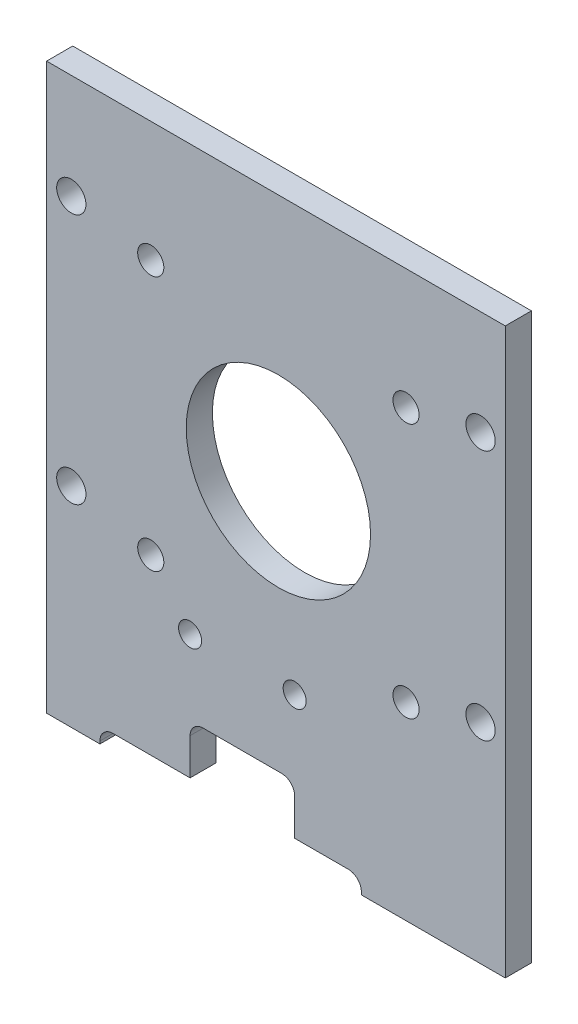
SolidWorks part; units mm, degrees
ref_plane "Front Plane" through (0, 0, 0) normal (0, 0, 1) x (1, 0, 0)
ref_plane "Top Plane" through (0, 0, 0) normal (0, 1, 0) x (1, 0, 0)
ref_plane "Right Plane" through (0, 0, 0) normal (1, 0, 0) x (0, 0, -1)
sketch "Sketch1" plane through (0, 0, 0) normal (0, 0, 1) x (1, 0, 0)
  line L1 (0, 0) -> (55.7007, 0)
  line L2 (0, 0) -> (0, 68.58)
  line L3 (0, 68.58) -> (55.7007, 68.58)
  line L4 (55.7007, 0) -> (55.7007, 68.58)
  dimension "D1" = 55.7007
  dimension "D2" = 68.58
extrude "Boss-Extrude1" add sketch "Sketch1" along normal blind 3.175
sketch "Sketch2" plane through (0, 0, 3.175) normal (0, 0, 1) x (1, 0, 0)
  line L0 (22.8992, 38.475) -> (24.6492, 38.475) construction
  line L1 (12.6492, 22.975) -> (43.6492, 22.975) construction
  line L2 (12.6492, 22.975) -> (12.6492, 53.975) construction
  line L3 (12.6492, 53.975) -> (43.6492, 53.975) construction
  line L4 (43.6492, 22.975) -> (43.6492, 53.975) construction
  line L5 (12.6492, 22.975) -> (43.6492, 53.975) construction
  line L6 (12.6492, 53.975) -> (43.6492, 22.975) construction
  line L7 (55.7007, 68.58) -> (0, 68.58) construction
  line L8 (0, 68.58) -> (0, 0) construction
  line L9 (23.7742, 38.475) -> (23.7742, 17.0053) construction
  line L10 (23.7742, 17.0053) -> (30.1242, 17.0053) construction
  line L11 (23.7742, 17.0053) -> (17.4242, 17.0053) construction
  line L13 (7.1492, 17.475) -> (49.1492, 17.475) construction
  line L14 (7.1492, 17.475) -> (7.1492, 59.475) construction
  line L15 (7.1492, 59.475) -> (49.1492, 59.475) construction
  line L16 (49.1492, 17.475) -> (49.1492, 59.475) construction
  line L17 (7.1492, 17.475) -> (49.1492, 59.475) construction
  line L18 (7.1492, 59.475) -> (49.1492, 17.475) construction
  line L20 (0, 0) -> (55.7007, 0) construction
  line L21 (17.4242, 0) -> (30.1242, 0)
  line L22 (17.4242, 0) -> (17.4242, 7.9375)
  line L23 (17.4242, 7.9375) -> (30.1242, 7.9375)
  line L24 (30.1242, 0) -> (30.1242, 7.9375)
  line L25 (23.7742, 17.0053) -> (23.7742, 7.9375) construction
  circle A0 centre (28.1492, 38.475) radius 11.1905
  circle A1 centre (12.6492, 53.975) radius 1.5875
  circle A2 centre (43.6492, 53.975) radius 1.5875
  circle A3 centre (43.6492, 22.975) radius 1.5875
  circle A4 centre (12.6492, 22.975) radius 1.5875
  circle A5 centre (11.8992, 38.475) radius 11 construction
  circle A6 centre (28.1492, 38.475) radius 3.5 construction
  circle A7 centre (17.4242, 17.0053) radius 1.397
  circle A8 centre (30.1242, 17.0053) radius 1.397
  dimension "D1" = 22.381
  dimension "D3" = 3.175
  dimension "D4" = 22
  dimension "D5" = 7
  dimension "D12" = 2.794
  dimension "D2" = 31
  dimension "D6" = 1.75
  dimension "D7" = 14.605
  dimension "D8" = 12.6492
  dimension "D9" = 42
  dimension "D10" = 12.7
  dimension "D11" = 5.9697
  dimension "D13" = 7.9375
  dimension "D14" = 12.7
extrude "Cut-Extrude1" cut sketch "Sketch2" against normal through all
sketch "Sketch3" plane through (0, 0, 3.175) normal (0, 0, 1) x (1, 0, 0)
  line L0 (0, 0) -> (17.4242, 0) construction
  line L1 (6.477, 0) -> (38.227, 0)
  line L2 (6.477, 0) -> (6.477, 1.905)
  line L3 (6.477, 1.905) -> (38.227, 1.905)
  line L4 (38.227, 0) -> (38.227, 1.905)
  line L5 (0, 68.58) -> (0, 0) construction
  dimension "D1" = 31.75
  dimension "D2" = 6.477
  dimension "D3" = 1.905
extrude "Cut-Extrude2" cut sketch "Sketch3" against normal through all
sketch "Sketch4" plane through (0, 0, 3.175) normal (0, 0, 1) x (1, 0, 0)
  line L0 (0, 68.58) -> (0, 0) construction
  line L1 (3, 55.88) -> (52.7007, 55.88) construction
  line L2 (3, 55.88) -> (3, 25.4) construction
  line L3 (3, 25.4) -> (52.7007, 25.4) construction
  line L4 (52.7007, 55.88) -> (52.7007, 25.4) construction
  line L5 (3, 55.88) -> (52.7007, 25.4) construction
  line L6 (3, 25.4) -> (52.7007, 55.88) construction
  line L7 (55.7007, 68.58) -> (0, 68.58) construction
  line L8 (55.7007, 0) -> (55.7007, 68.58) construction
  line L9 (0, 0) -> (6.477, 0) construction
  circle A0 centre (3, 55.88) radius 1.778
  circle A1 centre (3, 25.4) radius 1.778
  circle A2 centre (52.7007, 25.4) radius 1.778
  circle A3 centre (52.7007, 55.88) radius 1.778
  point P0 (27.8503, 40.64)
  dimension "D5" = 3.556
  dimension "D1" = 3
  dimension "D2" = 12.7
  dimension "D3" = 3
  dimension "D4" = 25.4
extrude "Cut-Extrude3" cut sketch "Sketch4" against normal through all
fillet "Fillet1" radius 1.5875 4 edges at (38.227, 1.905, 1.5875) (30.1242, 7.9375, 1.5875) (17.4242, 7.9375, 1.5875) (6.477, 1.905, 1.5875)
